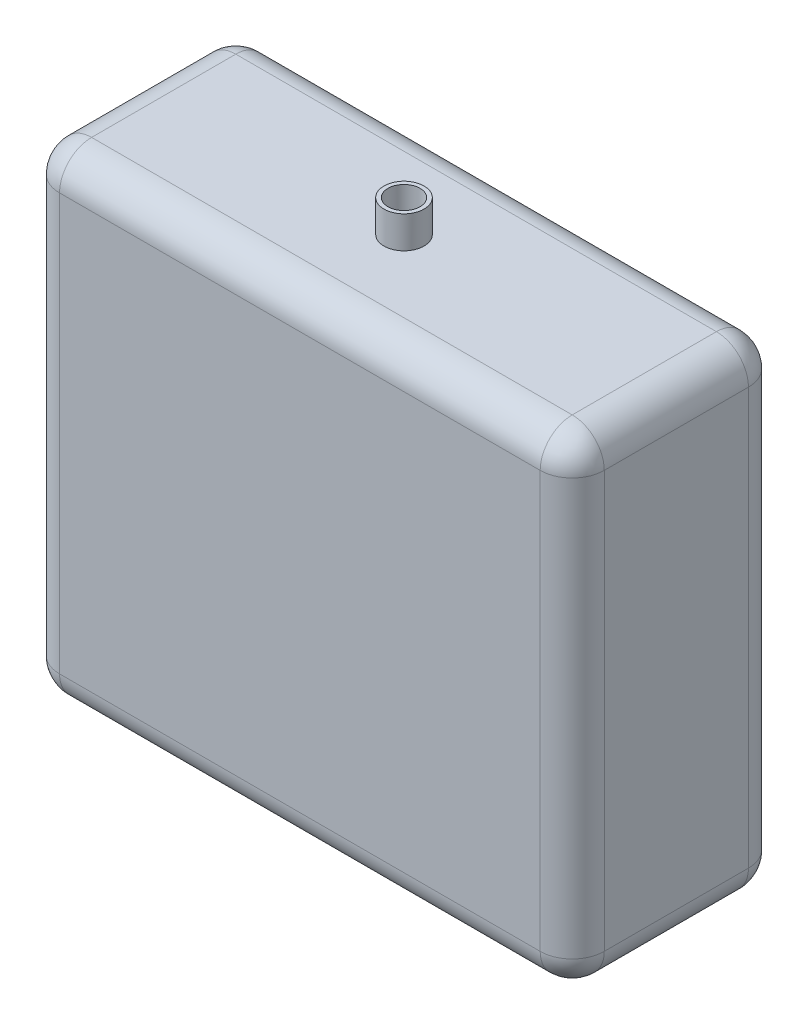
SolidWorks part; units mm, degrees
ref_plane "Front Plane" through (0, 0, 0) normal (0, 0, 1) x (1, 0, 0)
ref_plane "Top Plane" through (0, 0, 0) normal (0, 1, 0) x (1, 0, 0)
ref_plane "Right Plane" through (0, 0, 0) normal (1, 0, 0) x (0, 0, -1)
sketch "Sketch1" plane through (0, 0, 0) normal (0, 0, 1) x (1, 0, 0)
  line L5 (-170, -150) -> (170, -150)
  line L6 (-170, -150) -> (-170, 150)
  line L7 (-170, 150) -> (170, 150)
  line L8 (170, -150) -> (170, 150)
  line L9 (-170, -150) -> (170, 150) construction
  line L10 (-170, 150) -> (170, -150) construction
  point P0 (0, 0)
  dimension "D1" = 300
  dimension "D2" = 340
extrude "Boss-Extrude1" add sketch "Sketch1" along normal blind 130
fillet "Fillet1" radius 20 12 edges at (-170, 0, 0) (0, -150, 0) (170, -150, 65) (0, -150, 130) (170, 0, 0) (170, 0, 130) (-170, 0, 130) (-170, 150, 65) (0, 150, 0) (170, 150, 65) (0, 150, 130) (-170, -150, 65)
sketch "Sketch2" plane through (0, 150, 0) normal (0, 1, 0) x (1, 0, 0)
  line L0 (150, -20) -> (-150, -20) construction
  line L1 (-150, -110) -> (150, -110) construction
  circle A1 centre (0, -65) radius 12.5
  dimension "D4" = 25
  dimension "D2" = 45
  dimension "D3" = 45
extrude "Boss-Extrude2" add sketch "Sketch2" along normal blind 20
shell "Shell2" thickness 2.5
